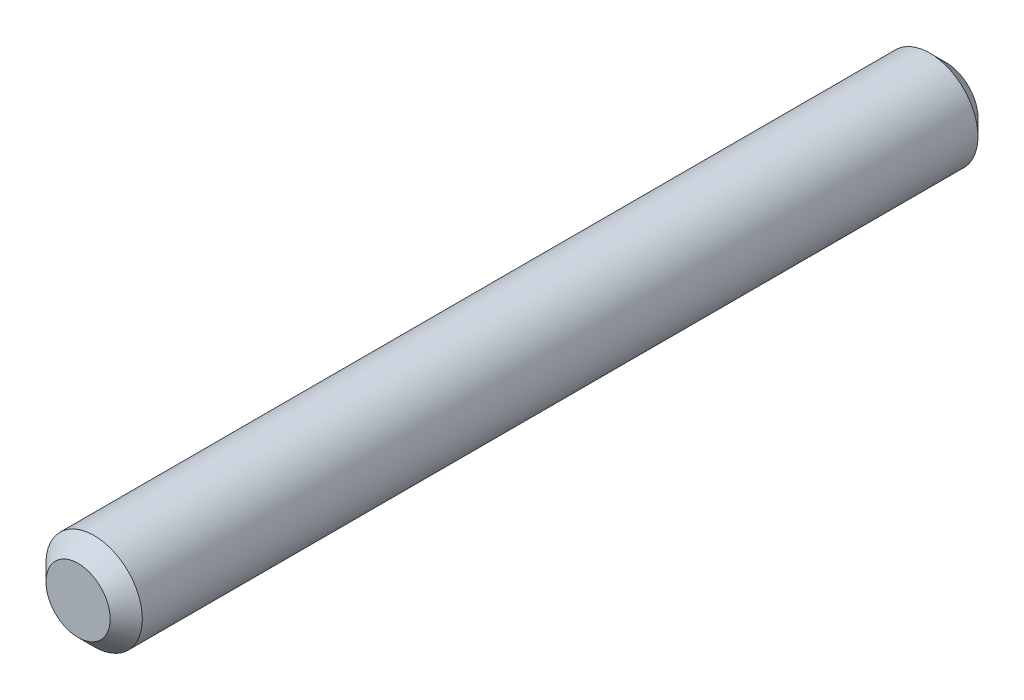
SolidWorks part; units mm, degrees
ref_plane "Piano frontale" through (0, 0, 0) normal (0, 0, 1) x (1, 0, 0)
ref_plane "Piano superiore" through (0, 0, 0) normal (0, 1, 0) x (1, 0, 0)
ref_plane "Piano destro" through (0, 0, 0) normal (1, 0, 0) x (0, 0, -1)
sketch "Schizzo1" plane through (0, 0, 0) normal (0, 0, 1) x (1, 0, 0)
  circle A0 centre (0, 0) radius 3
  dimension "D1" = 6
extrude "Estrusione-Estrusione1" add sketch "Schizzo1" along normal blind 54
chamfer "Smusso1" distance 1 angle 45 2 edges at (3, 0, 0) (3, 0, 54)
